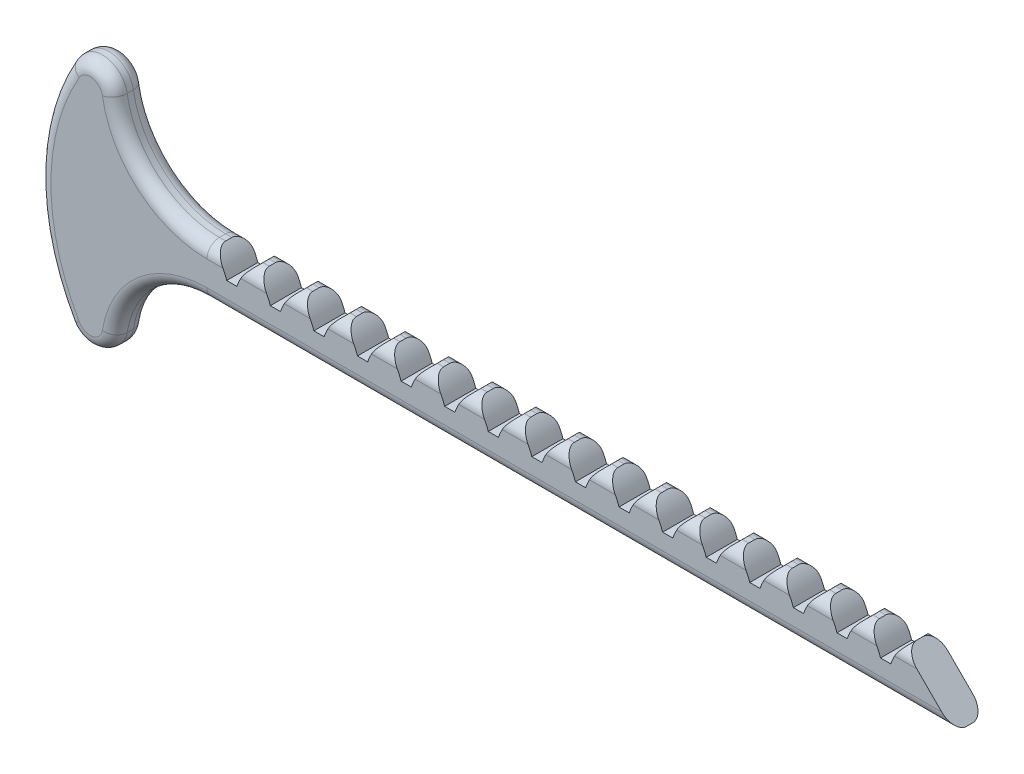
SolidWorks part; units mm, degrees
material "Plain Carbon Steel"
ref_plane "Front Plane" through (0, 0, 0) normal (0, 0, 1) x (1, 0, 0)
ref_plane "Top Plane" through (0, 0, 0) normal (0, 1, 0) x (1, 0, 0)
ref_plane "Right Plane" through (0, 0, 0) normal (1, 0, 0) x (0, 0, -1)
sketch "Sketch1" plane through (0, 0, 0) normal (0, 0, 1) x (1, 0, 0)
  line L0 (-38.1, 0) -> (38.1, 0)
  line L1 (38.1, 0) -> (33.02, 5.08)
  line L2 (33.02, 5.08) -> (-38.1, 5.08)
  arc A0 (-38.1, 5.08) -> (-47.5055, 13.1011) centre (-38.1, 14.605) cw
  arc A2 (-47.5055, -8.0211) -> (-38.1, 0) centre (-38.1, -9.525) cw
  arc A4 (-52.2134, 13.97) -> (-52.2134, -8.89) centre (-32.416, 2.54) ccw
  arc A5 (-52.2134, -8.89) -> (-47.5055, -8.0211) centre (-50.0137, -7.62) ccw
  arc A6 (-47.5055, 13.1011) -> (-52.2134, 13.97) centre (-50.0137, 12.7) ccw
  point P10 (0, 0)
  point P14 (35.56, 2.54)
  point P16 (0, 0)
  dimension "D1" = 45
  dimension "D2" = 5.08
  dimension "D4" = 2.54
  dimension "D5" = 9.525
  dimension "D6" = 22.86
  dimension "D7" = 25.4
  dimension "D3" = 76.2
extrude "Boss-Extrude1" add sketch "Sketch1" along normal mid plane 3.175
fillet "Fillet1" radius 1.27 14 edges at (-2.54, 5.08, 1.5875) (0, 0, 1.5875) (-44.2806, -2.2776, 1.5875) (-49.5526, -10.1178, 1.5875) (-55.276, 2.54, 1.5875) (-49.5526, 15.1978, 1.5875) (0, 0, -1.5875) (-2.54, 5.08, -1.5875) (-44.2806, 7.3576, -1.5875) (-49.5526, 15.1978, -1.5875) (-55.276, 2.54, -1.5875) (-49.5526, -10.1178, -1.5875) (-44.2806, -2.2776, -1.5875) (-44.2806, 7.3576, 1.5875)
sketch "Sketch3" plane through (0, 0, 0) normal (0, 0, 1) x (1, 0, 0)
  line L0 (-38.1, 5.08) -> (33.02, 5.08) construction
  line L1 (30.5929, 2.921) -> (31.6371, 2.921)
  line L2 (29.21, 5.08) -> (33.02, 5.08)
  line L3 (31.115, 5.08) -> (31.115, 2.921) construction
  arc A0 (33.02, 5.08) -> (31.6371, 2.921) centre (36.4678, 1.3492) ccw
  arc A1 (29.21, 5.08) -> (30.5929, 2.921) centre (25.7622, 1.3492) cw
  point P7 (31.115, 3.2312)
  dimension "D1" = 5.08
  dimension "D2" = 2.159
  dimension "D3" = 3.81
  dimension "D4" = 1.0442
extrude "Cut-Extrude1" cut sketch "Sketch3" against normal through all both and the other way through all
pattern_linear "LPattern1" count 16 spacing 4.445 along (-1, 0, 0) of "Cut-Extrude1"
